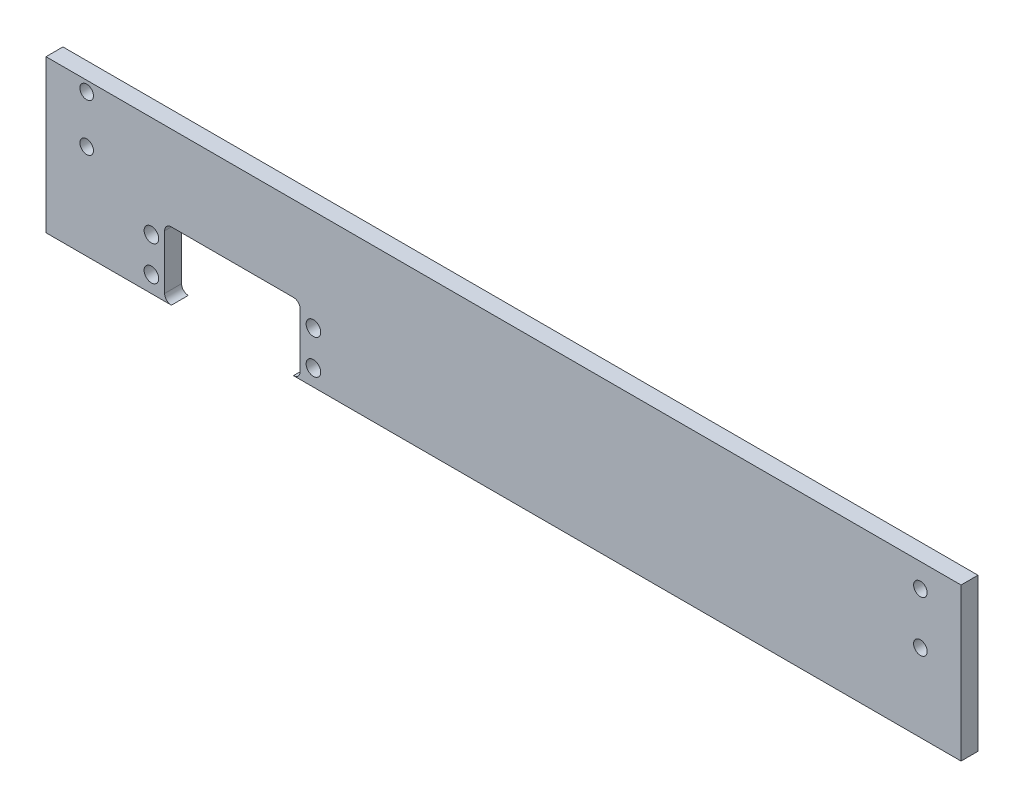
SolidWorks part; units mm, degrees
ref_plane "Plan de face" through (0, 0, 0) normal (0, 0, 1) x (1, 0, 0)
ref_plane "Plan de dessus" through (0, 0, 0) normal (0, 1, 0) x (1, 0, 0)
ref_plane "Plan de droite" through (0, 0, 0) normal (1, 0, 0) x (0, 0, -1)
sketch "Esquisse1" plane through (0, 0, 0) normal (0, 0, 1) x (1, 0, 0)
  line L1 (-135, 37.5) -> (135, 37.5)
  line L2 (-135, 37.5) -> (-135, -37.5)
  line L3 (-135, -37.5) -> (135, -37.5)
  line L4 (135, 37.5) -> (135, -37.5)
  line L5 (-135, 37.5) -> (135, -37.5) construction
  line L6 (-135, -37.5) -> (135, 37.5) construction
  point P0 (0, 0)
  dimension "D1" = 270
  dimension "D2" = 75
extrude "Boss.-Extru.1" add sketch "Esquisse1" along normal blind 5
sketch "Esquisse2" plane through (0, 0, 5) normal (0, 0, 1) x (1, 0, 0)
  line L0 (-135, -37.5) -> (135, -37.5) construction
  line L2 (-135, 37.5) -> (-135, -37.5) construction
  line L3 (135, -37.5) -> (135, 37.5) construction
  circle A0 centre (123, 0.5) radius 2
  circle A1 centre (123, -14.5) radius 2
  circle A2 centre (-123, 4.5) radius 2
  circle A3 centre (-123, -9.5) radius 2
  dimension "D9" = 4
  dimension "D10" = 4
  dimension "D11" = 4
  dimension "D12" = 4
  dimension "D1" = 28
  dimension "D2" = 42
  dimension "D3" = 23
  dimension "D4" = 38
  dimension "D5" = 12
  dimension "D6" = 12
  dimension "D7" = 12
  dimension "D8" = 12
extrude "Enlèv. mat.-Extru.1" cut sketch "Esquisse2" against normal through all
sketch "Esquisse3" plane through (0, 0, 5) normal (0, 0, 1) x (1, 0, 0)
  line L0 (-98, -37.5) -> (-62, -37.5)
  line L1 (-60, -35.5) -> (-60, -19.5)
  line L2 (-100, -19.5) -> (-100, -35.5)
  line L3 (-62, -17.5) -> (-98, -17.5)
  line L4 (-135, 37.5) -> (-135, -37.5) construction
  line L6 (-135, -37.5) -> (135, -37.5) construction
  arc A0 (-54.3875, -31.3) -> (-54.3875, -33.9) centre (-56.1, -32.6) ccw
  arc A1 (-54.3875, -21.1) -> (-54.3875, -23.7) centre (-56.1, -22.4) ccw
  arc A2 (-105.6125, -33.9) -> (-105.6125, -31.3) centre (-103.9, -32.6) ccw
  arc A3 (-105.6125, -23.7) -> (-105.6125, -21.1) centre (-103.9, -22.4) ccw
  arc A4 (-62, -37.5) -> (-60, -35.5) centre (-62, -35.5) ccw
  arc A5 (-100, -35.5) -> (-98, -37.5) centre (-98, -35.5) ccw
  arc A6 (-60, -19.5) -> (-62, -17.5) centre (-62, -19.5) ccw
  arc A7 (-98, -17.5) -> (-100, -19.5) centre (-98, -19.5) ccw
  arc A8 (-105.6125, -23.7) -> (-105.6125, -21.1) centre (-103.9, -22.4) cw
  arc A9 (-105.6125, -33.9) -> (-105.6125, -31.3) centre (-103.9, -32.6) cw
  arc A10 (-54.3875, -31.3) -> (-54.3875, -33.9) centre (-56.1, -32.6) cw
  arc A11 (-54.3875, -21.1) -> (-54.3875, -23.7) centre (-56.1, -22.4) cw
  dimension "D12" = 2
  dimension "D13" = 2
  dimension "D14" = 2
  dimension "D15" = 2
  dimension "D1" = 20
  dimension "D2" = 40
  dimension "D3" = 4.9
  dimension "D4" = 3.9
  dimension "D5" = 3.9
  dimension "D6" = 4.9
  dimension "D7" = 4.9
  dimension "D8" = 3.9
  dimension "D9" = 3.9
  dimension "D10" = 4.9
  dimension "D11" = 35
  dimension "D16" = 18
extrude "Enlèv. mat.-Extru.2" cut sketch "Esquisse3" against normal through all both and the other way through all
sketch "Esquisse4" plane through (0, 37.5, 0) normal (0, 1, 0) x (1, 0, 0)
  line L1 (135, 0) -> (-135, 0)
  line L2 (135, 0) -> (135, -5)
  line L3 (135, -5) -> (-135, -5)
  line L4 (-135, 0) -> (-135, -5)
extrude "Enlèv. mat.-Extru.3" cut sketch "Esquisse4" against normal blind 30
